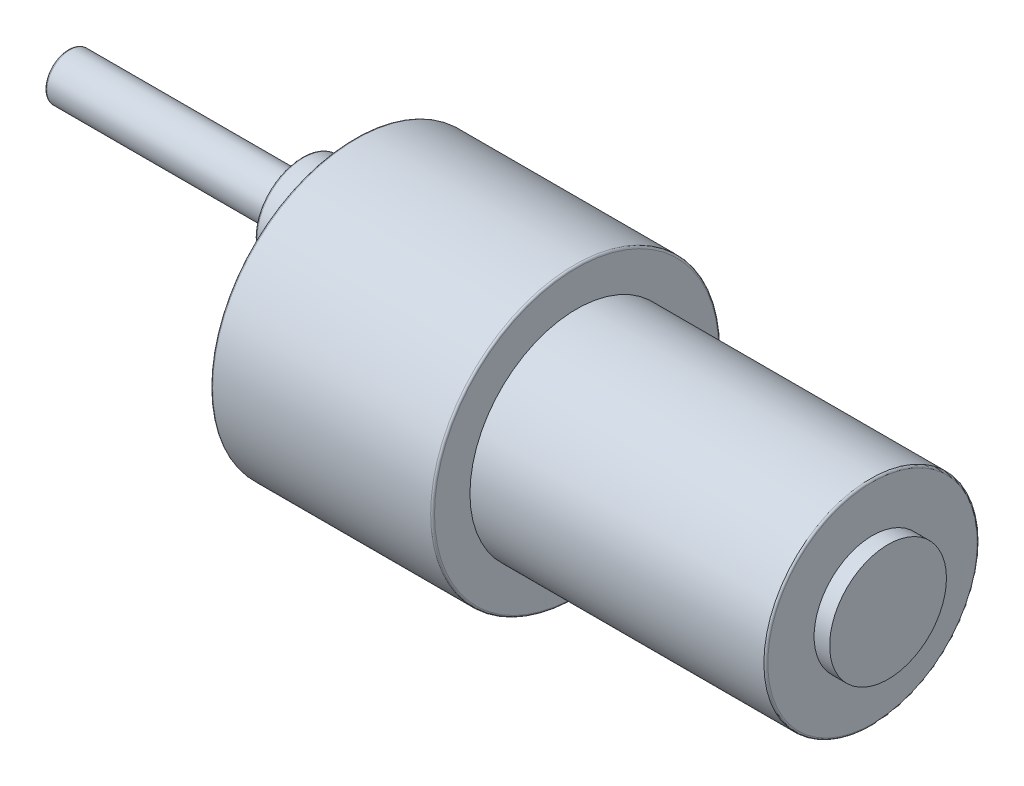
SolidWorks part; units mm, degrees
ref_plane "Front Plane" through (0, 0, 0) normal (0, 0, 1) x (1, 0, 0)
ref_plane "Top Plane" through (0, 0, 0) normal (0, 1, 0) x (1, 0, 0)
ref_plane "Right Plane" through (0, 0, 0) normal (1, 0, 0) x (0, 0, -1)
sketch "Sketch1" plane through (0, 0, 0) normal (1, 0, 0) x (0, 0, -1)
  circle A0 centre (0, 0) radius 18.5
  dimension "D1" = 37
extrude "Boss-Extrude1" add sketch "Sketch1" along normal blind 28.5
sketch "Sketch2" plane through (28.5, 0, 0) normal (1, 0, 0) x (0, 0, -1)
  circle A0 centre (0, 0) radius 13.7
  dimension "D1" = 27.4
extrude "Boss-Extrude2" add sketch "Sketch2" along normal blind 38
sketch "Sketch3" plane through (66.5, 0, 0) normal (1, 0, 0) x (0, 0, -1)
  circle A0 centre (0, 0) radius 7.5
  dimension "D1" = 15
extrude "Boss-Extrude3" add sketch "Sketch3" along normal blind 2
sketch "Sketch4" plane through (0, 0, 0) normal (-1, 0, 0) x (0, 0, 1)
  line L0 (0, 0) -> (0, 15.75) construction
  line L1 (0, 0) -> (13.6399, 7.875) construction
  line L2 (0, 0) -> (13.6399, -7.875) construction
  line L3 (0, 0) -> (0, -15.75) construction
  line L4 (0, 0) -> (-13.6399, -7.875) construction
  line L5 (0, 0) -> (-13.6399, 7.875) construction
  point P10 (0, 0)
  dimension "D1" = 15.75
  dimension "D2" = 6
hole_wizard "Tap Drill for M3x0.5 Tap1" positions "3DSketch1" profile "Sketch5" hole size "M3x0.5" standard "ANSI Metric"
sketch3d "3DSketch1"
  point P0 (0, 15.75, 0)
  point P3 (0, 7.875, 13.6399)
  point P6 (0, -7.875, 13.6399)
  point P9 (0, -15.75, 0)
  point P12 (0, -7.875, -13.6399)
  point P15 (0, 7.875, -13.6399)
sketch "Sketch5" plane through (0, 15.75, 0) normal (0, 1, 0) x (0, 0, 1)
  line L0 (0, 0) -> (0, 5.7511)
  line L1 (0, 5.7511) -> (1.25, 5)
  line L2 (1.25, 5) -> (1.25, 0)
  line L5 (1.25, 0) -> (0, 0)
  line L10 (0, 5.7511) -> (-1.25, 5) construction
  line L11 (0, -6.35) -> (0, 107.95) construction
  dimension "Hole Dia." = 2.5
  dimension "Hole Depth" = 5
  dimension "Drill Angle" = 118
sketch "Sketch6" plane through (0, 0, 0) normal (-1, 0, 0) x (0, 0, 1)
  line L0 (0, 0) -> (0, 7) construction
  circle A0 centre (0, 7) radius 6
  dimension "D1" = 7
extrude "Boss-Extrude4" add sketch "Sketch6" along normal blind 6.8
sketch "Sketch7" plane through (-6.8, 0, 0) normal (-1, 0, 0) x (0, 0, 1)
  circle A0 centre (0, 7) radius 3
  dimension "D1" = 6
extrude "Boss-Extrude5" add sketch "Sketch7" along normal blind 30
fillet "Fillet1" radius 0.25 7 edges at (66.5, 0, -13.7) (28.5, 0, -18.5) (0, 0, -18.5) (0, 7, -6) (-6.8, 7, 6) (-6.8, 7, 3) (-36.8, 7, 3)
